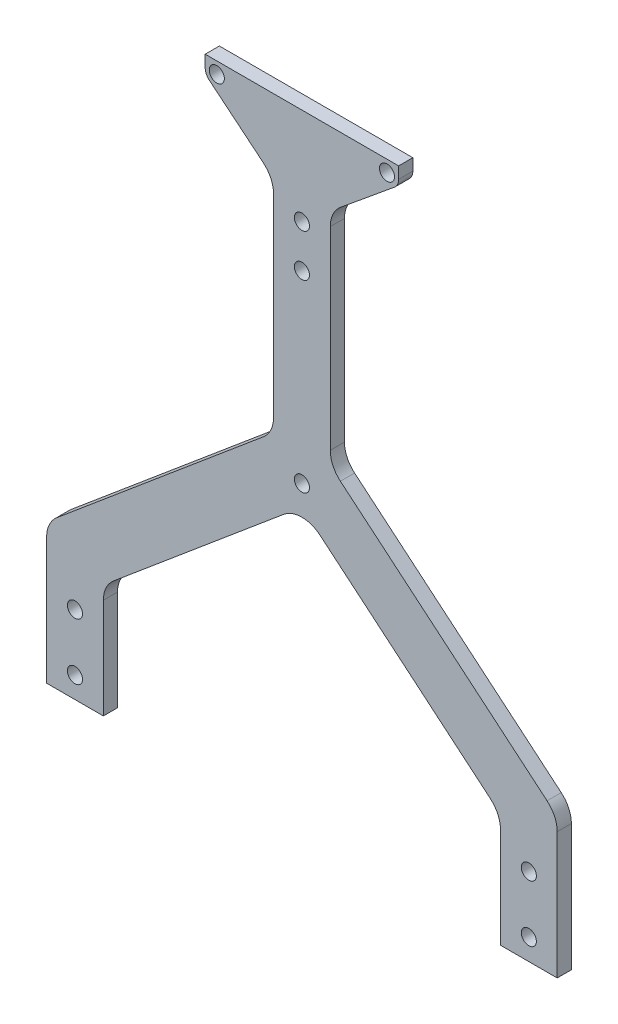
SolidWorks part; units mm, degrees
ref_plane "Front Plane" through (0, 0, 0) normal (0, 0, 1) x (1, 0, 0)
ref_plane "Top Plane" through (0, 0, 0) normal (0, 1, 0) x (1, 0, 0)
ref_plane "Right Plane" through (0, 0, 0) normal (1, 0, 0) x (0, 0, -1)
sketch "Sketch1" plane through (0, 0, 0) normal (0, 0, 1) x (1, 0, 0)
  line L0 (-88.9, 0) -> (88.9, 0) construction
  line L1 (-88.9, 0) -> (-114.3, 0)
  line L2 (-114.3, 0) -> (-114.3, 62.6442)
  line L3 (-88.9, 0) -> (-88.9, 50.8)
  line L4 (-88.9, 50.8) -> (-25.4, 104.0828)
  line L5 (-88.9, 50.8) -> (-114.3, 62.6442) construction
  line L6 (-114.3, 62.6442) -> (-41.7268, 123.5404)
  line L7 (-41.7268, 123.5404) -> (-12.7, 147.8967)
  line L8 (-25.4, 104.0828) -> (0, 125.396)
  line L9 (0, 125.396) -> (0, 278.1608) construction
  line L10 (-25.4, 104.0828) -> (-41.7268, 123.5404) construction
  line L11 (-12.7, 147.8967) -> (-12.7, 279.4)
  line L12 (-12.7, 279.4) -> (12.7, 279.4)
  line L13 (25.4, 104.0828) -> (41.7268, 123.5404) construction
  line L14 (88.9, 50.8) -> (114.3, 62.6442) construction
  line L15 (12.7, 147.8967) -> (12.7, 279.4)
  line L16 (25.4, 104.0828) -> (0, 125.396)
  line L17 (41.7268, 123.5404) -> (12.7, 147.8967)
  line L18 (114.3, 62.6442) -> (41.7268, 123.5404)
  line L19 (88.9, 50.8) -> (25.4, 104.0828)
  line L20 (88.9, 0) -> (88.9, 50.8)
  line L21 (114.3, 0) -> (114.3, 62.6442)
  line L22 (88.9, 0) -> (114.3, 0)
  point P2 (0, 0)
  point P19 (0, 279.4)
  dimension "D1" = 177.8
  dimension "D2" = 115
  dimension "D3" = 115
  dimension "D4" = 50.8
  dimension "D5" = 25.4
  dimension "D6" = 90
  dimension "D7" = 90
  dimension "D8" = 25.4
  dimension "D9" = 12.7
  dimension "D10" = 279.4
extrude "Boss-Extrude1" add sketch "Sketch1" along normal mid plane 6.35
fillet "Fillet1" radius 12.7 7 edges at (-12.7, 147.8967, 0) (12.7, 147.8967, 0) (-114.3, 62.6442, 0) (114.3, 62.6442, 0) (88.9, 50.8, 0) (0, 125.396, 0) (-88.9, 50.8, 0)
hole_wizard "1/4 Clearance Hole1" positions "Sketch2" profile "Sketch3" hole size "1/4" standard "ANSI Inch" end condition through all
sketch "Sketch2" plane through (0, 0, 3.175) normal (0, 0, 1) x (1, 0, 0)
  line L0 (-101.6, 0) -> (-101.6, 73.3008) construction
  line L1 (-114.3, 0) -> (-88.9, 0) construction
  line L2 (-17.2366, 144.0901) -> (-109.7634, 66.4509) construction
  line L4 (101.6, 0) -> (101.6, 73.3008) construction
  line L5 (88.9, 0) -> (114.3, 0) construction
  line L6 (109.7634, 66.4509) -> (17.2366, 144.0901) construction
  line L7 (-101.6, 9.525) -> (101.6, 9.525) construction
  line L9 (-101.6, 34.925) -> (101.6, 34.925) construction
  point P16 (-101.6, 9.525)
  point P18 (-101.6, 34.925)
  point P22 (101.6, 9.525)
  point P26 (101.6, 34.925)
  dimension "D1" = 9.525
  dimension "D2" = 25.4
sketch "Sketch3" plane through (101.6, 34.925, 3.175) normal (1, 0, 0) x (0, -1, 0)
  line L0 (0, 0) -> (0, 6.35)
  line L1 (0, 6.35) -> (3.3782, 6.35)
  line L2 (3.3782, 6.35) -> (3.3782, 0)
  line L5 (3.3782, 0) -> (0, 0)
  line L11 (0, -6.35) -> (0, 107.95) construction
  dimension "Thru Hole Dia." = 6.7564
  dimension "Thru Hole Depth" = 6.35
hole_wizard "1/4 Clearance Hole2" positions "Sketch4" profile "Sketch5" hole size "1/4" standard "ANSI Inch"
sketch "Sketch4" plane through (0, 0, 6.35) normal (0, 0, 1) x (1, 0, 0)
  line L0 (0, 279.4) -> (0, 244.475) construction
  line L1 (12.7, 279.4) -> (-12.7, 279.4) construction
  point P1 (0, 244.475)
  point P9 (0, 263.525)
  dimension "D1" = 34.925
  dimension "D2" = 19.05
sketch "Sketch5" plane through (0, 263.525, 6.35) normal (1, 0, 0) x (0, -1, 0)
  line L0 (0, 0) -> (0, 12.7)
  line L1 (0, 12.7) -> (3.3782, 12.7)
  line L2 (3.3782, 12.7) -> (3.3782, 0)
  line L5 (3.3782, 0) -> (0, 0)
  line L11 (0, -6.35) -> (0, 107.95) construction
  dimension "Thru Hole Dia." = 6.7564
  dimension "Thru Hole Depth" = 12.7
hole_wizard "1/4 Clearance Hole3" positions "Sketch6" profile "Sketch8" hole size "1/4" standard "ANSI Inch" end condition through all
sketch "Sketch6" plane through (0, 0, -3.175) normal (0, 0, -1) x (-1, 0, 0)
  circle A0 centre (0, 134.62) radius 2.5527 construction
  circle A1 centre (0, 134.62) radius 2.5527
  point P1 (0, 134.62)
sketch "Sketch8" plane through (0, 134.62, -3.175) normal (1, 0, 0) x (0, 1, 0)
  line L0 (0, 0) -> (0, 6.35)
  line L1 (0, 6.35) -> (3.3782, 6.35)
  line L2 (3.3782, 6.35) -> (3.3782, 0)
  line L5 (3.3782, 0) -> (0, 0)
  line L11 (0, -6.35) -> (0, 107.95) construction
  dimension "Thru Hole Dia." = 6.7564
  dimension "Thru Hole Depth" = 6.35
hole_wizard "1/4 Clearance Hole4" positions "Sketch9" profile "Sketch10" hole size "1/4" standard "ANSI Inch" end condition through all
sketch "Sketch9" plane through (0, 0, 3.175) normal (0, 0, 1) x (1, 0, 0)
  point P0 (0, 217.0468)
sketch "Sketch10" plane through (0, 217.0468, 3.175) normal (1, 0, 0) x (0, -1, 0)
  line L0 (0, 0) -> (0, 6.35)
  line L1 (0, 6.35) -> (3.3782, 6.35)
  line L2 (3.3782, 6.35) -> (3.3782, 0)
  line L5 (3.3782, 0) -> (0, 0)
  line L11 (0, -6.35) -> (0, 107.95) construction
  dimension "Thru Hole Dia." = 6.7564
  dimension "Thru Hole Depth" = 6.35
sketch "Sketch11" plane through (0, 0, 3.175) normal (0, 0, 1) x (1, 0, 0)
  line L0 (-43.3032, 279.4) -> (43.3032, 279.4)
  line L2 (41.4067, 270.1796) -> (2.6083, 238.2438)
  line L3 (-2.6083, 238.2438) -> (-41.4067, 270.1796)
  line L4 (0, 236.0968) -> (0, 279.4) construction
  line L5 (12.7, 279.4) -> (-12.7, 279.4) construction
  line L6 (0, 217.0468) -> (0, 236.0968) construction
  line L7 (38.1, 274.1968) -> (38.1, 279.4) construction
  line L8 (38.1, 274.1968) -> (41.4067, 270.1796) construction
  line L9 (-43.3032, 274.1968) -> (-43.3032, 279.4)
  line L10 (43.3032, 274.1968) -> (43.3032, 279.4)
  circle A0 centre (-38.1, 274.1968) radius 3.3782
  circle A1 centre (38.1, 274.1968) radius 3.3782
  circle A2 centre (0, 217.0468) radius 3.3782 construction
  circle A3 centre (0, 217.0468) radius 3.3782
  arc A4 (-43.3032, 274.1968) -> (-41.4067, 270.1796) centre (-38.1, 274.1968) ccw
  circle A6 centre (0, 236.0968) radius 3.3782 construction
  arc A7 (-2.6083, 238.2438) -> (2.6083, 238.2438) centre (0, 236.0968) cw
  arc A8 (-43.3032, 274.1968) -> (-45.1996, 270.1796) centre (-48.5063, 274.1968) cw
  arc A9 (43.3032, 274.1968) -> (41.4067, 270.1796) centre (38.1, 274.1968) cw
  point P3 (0, 279.4)
  dimension "D1" = 38.1
  dimension "D2" = 38.1
  dimension "D3" = 19.05
extrude "Boss-Extrude2" add sketch "Sketch11" against normal up to surface (6.35 mm away)
fillet "Fillet2" radius 12.7 2 edges at (-12.7, 246.5505, 0) (12.7, 246.5505, 0)
sketch "Sketch12" plane through (0, 0, 3.175) normal (0, 0, 1) x (1, 0, 0)
  circle A0 centre (0, 236.0968) radius 3.3782 construction
  circle A1 centre (0, 236.0968) radius 3.3782
extrude "Cut-Extrude1" cut sketch "Sketch12" against normal through all
equation "\"D3@Sketch1\"=\"D2@Sketch1\""
equation "\"D7@Sketch1\"=\"D6@Sketch1\""
